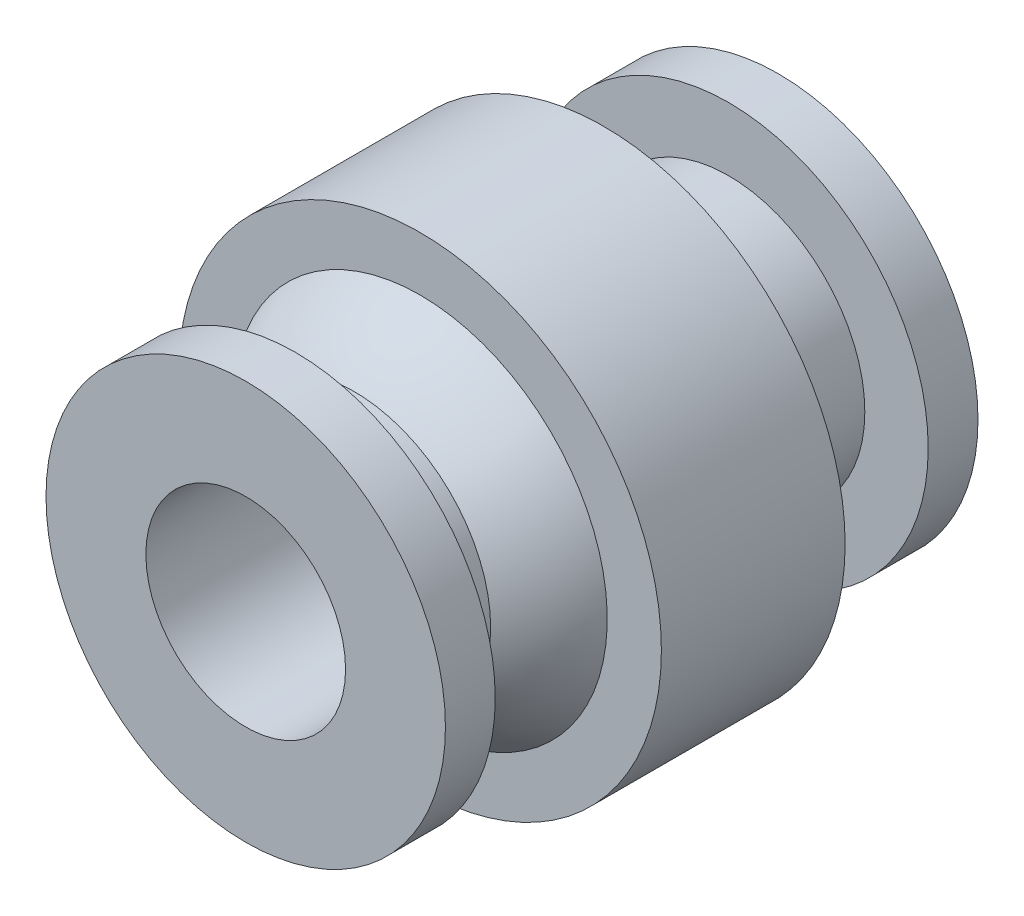
SolidWorks part; units mm, degrees
material "Alloy Steel"
ref_plane "X-Y Datum" through (0, 0, 0) normal (0, 0, 1) x (1, 0, 0)
ref_plane "X-Z Datum" through (0, 0, 0) normal (0, 1, 0) x (1, 0, 0)
ref_plane "Y-Z Datum" through (0, 0, 0) normal (1, 0, 0) x (0, 0, -1)
sketch "Sketch1" plane through (0, 0, 0) normal (1, 0, 0) x (0, 0, -1)
  line L0 (82.1362, -22.0492) -> (50082.1362, -22.0492) construction
  line L1 (71.12, -5.2479) -> (71.12, 49994.7521) construction
  line L2 (66.7385, -30.973) -> (71.12, -22.0492) construction
  line L3 (71.12, -22.0492) -> (63.6, -28.5516) construction
  line L4 (60.7949, -26.8117) -> (81.4451, -26.8117)
  line L5 (60.7949, -28.5516) -> (63.6, -28.5516)
  line L6 (66.7385, -30.973) -> (66.7385, -33.5554)
  line L7 (66.7385, -33.5554) -> (75.5015, -33.5554)
  line L8 (75.5015, -33.5554) -> (75.5015, -30.973)
  line L11 (78.64, -28.5516) -> (81.4451, -28.5516)
  line L28 (81.4451, -28.5516) -> (81.4451, -26.8117) construction
  line L31 (60.7949, -26.8117) -> (58.42, -26.8117)
  line L32 (58.42, -26.8117) -> (58.42, -31.5742)
  line L33 (58.42, -31.5742) -> (60.7949, -31.5742)
  line L34 (60.7949, -31.5742) -> (60.7949, -28.5516)
  line L35 (81.4451, -28.5516) -> (81.4451, -31.5742)
  line L36 (81.4451, -31.5742) -> (83.82, -31.5742)
  line L37 (83.82, -31.5742) -> (83.82, -26.8117)
  line L38 (83.82, -26.8117) -> (81.4451, -26.8117)
  arc A0 (63.6, -28.5516) -> (66.7385, -30.973) centre (71.12, -22.0492) ccw
  arc A1 (75.5015, -30.973) -> (78.64, -28.5516) centre (71.12, -22.0492) ccw
  point P8 (71.12, -26.8117)
  point P15 (71.12, -33.5554)
  dimension "D1" = 9.525
  dimension "D3" = 8.763
  dimension "D5" = 23
  dimension "D2" = 13.0048
  dimension "D4" = 20.6502
  dimension "D6" = 23.0124
  dimension "D7" = 25.4
  dimension "D9" = 19.05
  dimension "D10" = 19.05
revolve "Revolve1" add sketch "Sketch1" angle 360 about L0
